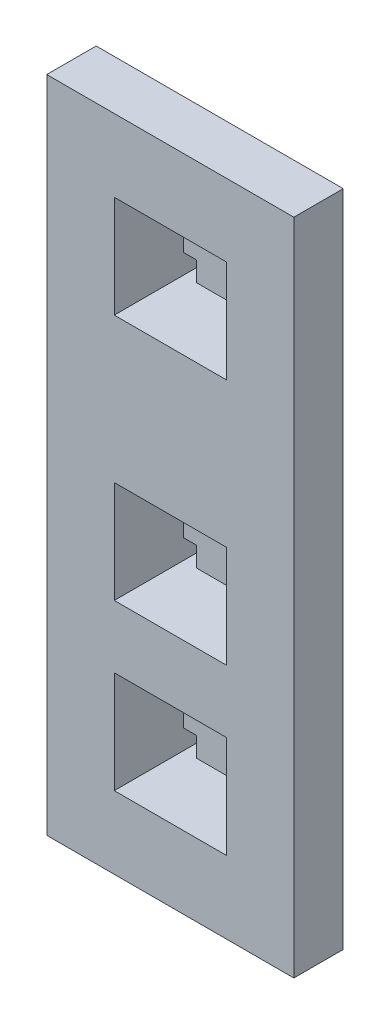
SolidWorks part; units mm, degrees
ref_plane "Plan de face" through (0, 0, 0) normal (0, 0, 1) x (1, 0, 0)
ref_plane "Plan de dessus" through (0, 0, 0) normal (0, 1, 0) x (1, 0, 0)
ref_plane "Plan de droite" through (0, 0, 0) normal (1, 0, 0) x (0, 0, -1)
sketch "Esquisse1" plane through (0, 0, 0) normal (0, 0, 1) x (1, 0, 0)
  line L1 (-7.5, 20) -> (7.5, 20)
  line L2 (-7.5, 20) -> (-7.5, -20)
  line L3 (-7.5, -20) -> (7.5, -20)
  line L4 (7.5, 20) -> (7.5, -20)
  line L5 (-7.5, 20) -> (7.5, -20) construction
  line L6 (-7.5, -20) -> (7.5, 20) construction
  point P0 (0, 0)
  dimension "D1" = 15
  dimension "D2" = 40
extrude "Boss.-Extru.1" add sketch "Esquisse1" along normal blind 5
sketch "Esquisse2" plane through (0, 0, 5) normal (0, 0, 1) x (1, 0, 0)
  line L0 (0, 12.5) -> (0, -2.5) construction
  line L1 (-3.4, 0.6) -> (3.4, 0.6)
  line L2 (-3.4, 0.6) -> (-3.4, -5.6)
  line L3 (-3.4, -5.6) -> (3.4, -5.6)
  line L4 (3.4, 0.6) -> (3.4, -5.6)
  line L5 (-3.4, 0.6) -> (3.4, -5.6) construction
  line L6 (-3.4, -5.6) -> (3.4, 0.6) construction
  line L7 (-3.4, 15.6) -> (3.4, 15.6)
  line L8 (-3.4, 15.6) -> (-3.4, 9.4)
  line L9 (-3.4, 9.4) -> (3.4, 9.4)
  line L10 (3.4, 15.6) -> (3.4, 9.4)
  line L11 (-3.4, 15.6) -> (3.4, 9.4) construction
  line L12 (-3.4, 9.4) -> (3.4, 15.6) construction
  line L13 (-3.4, -9.4) -> (3.4, -9.4)
  line L14 (-3.4, -9.4) -> (-3.4, -15.6)
  line L15 (-3.4, -15.6) -> (3.4, -15.6)
  line L16 (3.4, -9.4) -> (3.4, -15.6)
  line L17 (-3.4, -9.4) -> (3.4, -15.6) construction
  line L18 (-3.4, -15.6) -> (3.4, -9.4) construction
  line L19 (0, -2.5) -> (0, -12.5) construction
  line L20 (0, 12.5) -> (0, 20) construction
  line L21 (7.5, 20) -> (-7.5, 20) construction
  line L24 (-7.5, -20) -> (7.5, -20) construction
  line L25 (0, -20) -> (0, -12.5) construction
  point P6 (0, 12.5)
  point P11 (0, -12.5)
  dimension "D1" = 6.2
  dimension "D2" = 6.8
  dimension "D3" = 15
  dimension "D4" = 10
extrude "Enlèv. mat.-Extru.1" cut sketch "Esquisse2" against normal blind 4.2
sketch "Esquisse3" plane through (0, 0, 0.8) normal (0, 0, 1) x (1, 0, 0)
  line L0 (-3.4, 9.4) -> (3.4, 9.4) construction
  line L1 (-3.4, 0.6) -> (-2.6, 0.6)
  line L2 (-3.4, 0.6) -> (-3.4, -0.6)
  line L3 (-3.4, -0.6) -> (-2.6, -0.6)
  line L4 (-2.6, 0.6) -> (-2.6, -0.6)
  line L5 (-3.4, 9.4) -> (-2.6, 9.4)
  line L6 (-3.4, 9.4) -> (-3.4, 10.6)
  line L7 (-3.4, 10.6) -> (-2.6, 10.6)
  line L8 (-2.6, 9.4) -> (-2.6, 10.6)
  line L9 (3.4, -5.6) -> (3.4, 0.6) construction
  line L10 (-3.4, 15.6) -> (-2.6, 15.6)
  line L11 (-3.4, 15.6) -> (-3.4, 14.4)
  line L12 (-3.4, 14.4) -> (-2.6, 14.4)
  line L13 (-2.6, 15.6) -> (-2.6, 14.4)
  line L14 (3.4, 15.6) -> (2.6, 15.6)
  line L15 (3.4, 15.6) -> (3.4, 14.4)
  line L16 (3.4, 14.4) -> (2.6, 14.4)
  line L17 (2.6, 15.6) -> (2.6, 14.4)
  line L18 (3.4, 9.4) -> (2.6, 9.4)
  line L19 (3.4, 9.4) -> (3.4, 10.6)
  line L20 (3.4, 10.6) -> (2.6, 10.6)
  line L21 (2.6, 9.4) -> (2.6, 10.6)
  line L22 (3.4, 0.6) -> (2.6, 0.6)
  line L23 (3.4, 0.6) -> (3.4, -0.6)
  line L24 (3.4, -0.6) -> (2.6, -0.6)
  line L25 (2.6, 0.6) -> (2.6, -0.6)
  line L26 (3.4, -5.6) -> (2.6, -5.6)
  line L27 (3.4, -5.6) -> (3.4, -4.4)
  line L28 (3.4, -4.4) -> (2.6, -4.4)
  line L29 (2.6, -5.6) -> (2.6, -4.4)
  line L31 (3.4, -15.6) -> (2.6, -15.6)
  line L32 (3.4, -15.6) -> (3.4, -14.4)
  line L33 (3.4, -14.4) -> (2.6, -14.4)
  line L34 (2.6, -15.6) -> (2.6, -14.4)
  line L35 (3.4, -9.4) -> (2.6, -9.4)
  line L36 (3.4, -9.4) -> (3.4, -10.6)
  line L37 (3.4, -10.6) -> (2.6, -10.6)
  line L38 (2.6, -9.4) -> (2.6, -10.6)
  line L39 (-3.4, -9.4) -> (-2.6, -9.4)
  line L40 (-3.4, -9.4) -> (-3.4, -10.6)
  line L41 (-3.4, -10.6) -> (-2.6, -10.6)
  line L42 (-2.6, -9.4) -> (-2.6, -10.6)
  line L43 (-3.4, -15.6) -> (-2.6, -15.6)
  line L44 (-3.4, -15.6) -> (-3.4, -14.4)
  line L45 (-3.4, -14.4) -> (-2.6, -14.4)
  line L46 (-2.6, -15.6) -> (-2.6, -14.4)
  line L47 (-3.4, -5.6) -> (-2.6, -5.6)
  line L48 (-3.4, -5.6) -> (-3.4, -4.4)
  line L49 (-3.4, -4.4) -> (-2.6, -4.4)
  line L50 (-2.6, -5.6) -> (-2.6, -4.4)
  dimension "D1" = 0.8
  dimension "D2" = 1.2
extrude "Enlèv. mat.-Extru.2" cut sketch "Esquisse3" against normal through all
chamfer "Chanfrein1" distance 2 angle 45 4 edges at (-7.5, 0, 0) (0, -20, 0) (7.5, 0, 0) (0, 20, 0)
